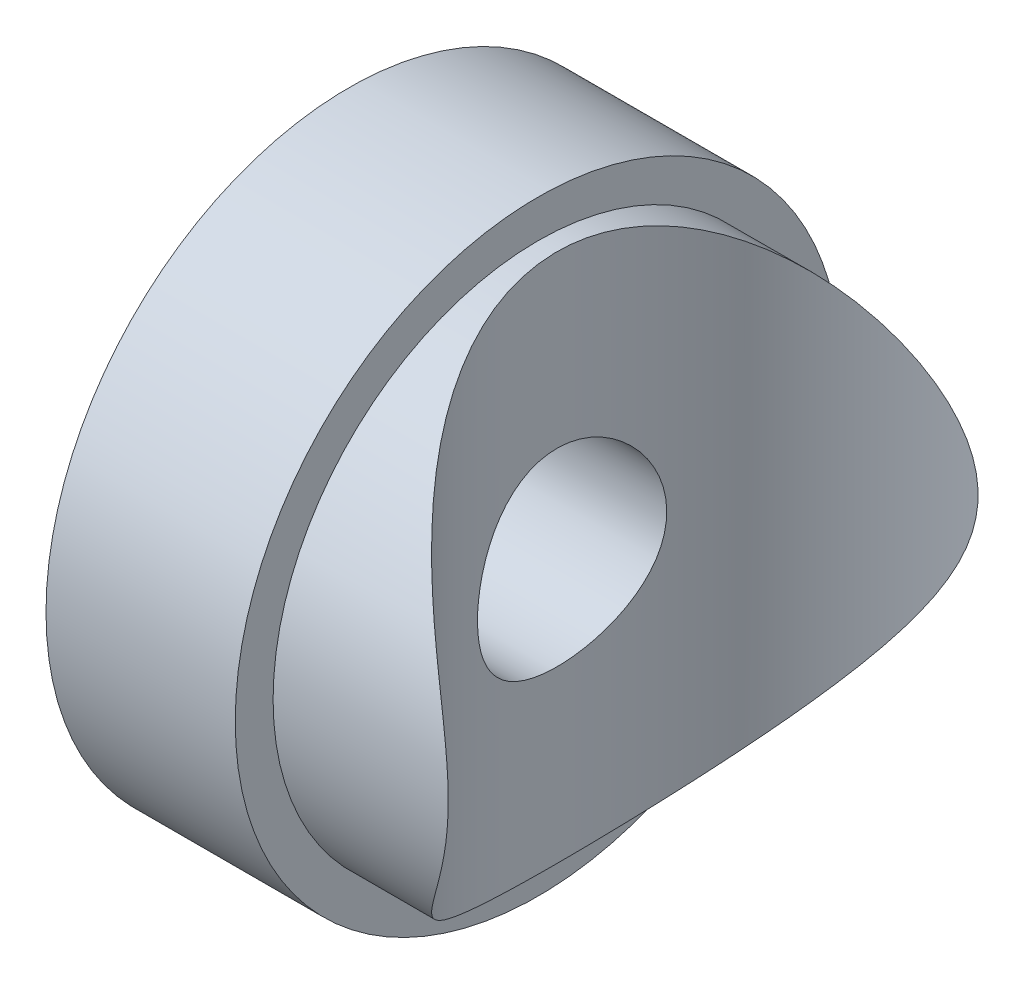
SolidWorks part; units mm, degrees
material "1023 Carbon Steel Sheet (SS)"
ref_plane "Front Plane" through (0, 0, 0) normal (0, 0, 1) x (1, 0, 0)
ref_plane "Top Plane" through (0, 0, 0) normal (0, 1, 0) x (1, 0, 0)
ref_plane "Right Plane" through (0, 0, 0) normal (1, 0, 0) x (0, 0, -1)
sketch "Sketch1" plane through (0, 0, 0) normal (1, 0, 0) x (0, 0, -1)
  circle A0 centre (0, 0) radius 8
  dimension "D1" = 16
extrude "Boss-Extrude1" add sketch "Sketch1" along normal blind 5 contours A0
sketch "Sketch2" plane through (5, 0, 0) normal (1, 0, 0) x (0, 0, -1)
  circle A2 centre (0, 0) radius 7
  circle A3 centre (0, 0) radius 7
  dimension "D1" = 1
extrude "Boss-Extrude2" add sketch "Sketch2" along normal blind 5
sketch "Sketch3" plane through (0, 0, 0) normal (0, 1, 0) x (1, 0, 0)
  line L0 (5, -7) -> (5, 7) construction
  circle A0 centre (13.5, 0) radius 8
  dimension "D1" = 16
  dimension "D2" = 8.5
  dimension "D3" = 13.5
extrude "Cut-Extrude1" cut sketch "Sketch3" against normal blind 15 and the other way through all
sketch "Sketch4" plane through (0, 0, 0) normal (-1, 0, 0) x (0, 0, 1)
  circle A0 centre (0, 0) radius 2.5
  dimension "D1" = 5
extrude "Cut-Extrude2" cut sketch "Sketch4" against normal blind 15
